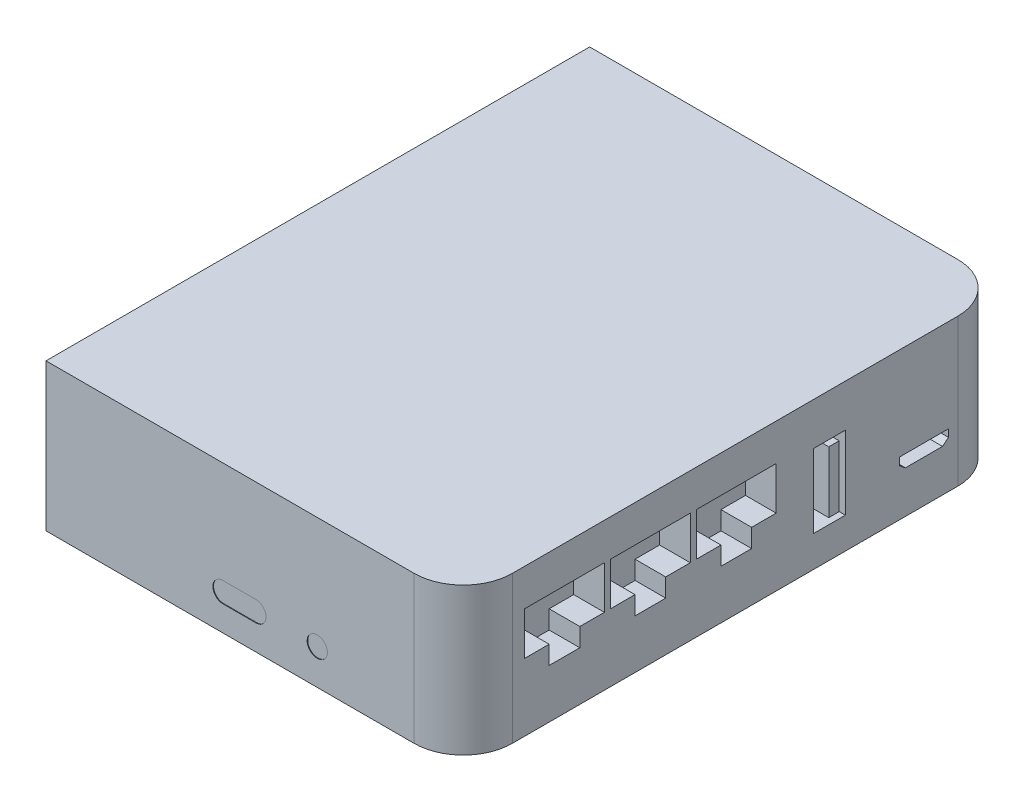
SolidWorks part; units mm, degrees
ref_plane "Plan de face" through (0, 0, 0) normal (0, 0, 1) x (1, 0, 0)
ref_plane "Plan de dessus" through (0, 0, 0) normal (0, 1, 0) x (1, 0, 0)
ref_plane "Plan de droite" through (0, 0, 0) normal (1, 0, 0) x (0, 0, -1)
sketch "Esquisse1" plane through (0, 0, 0) normal (0, 1, 0) x (1, 0, 0)
  line L1 (-34, 44.3) -> (34, 44.3)
  line L2 (-34, 44.3) -> (-34, -44.3)
  line L3 (-34, -44.3) -> (34, -44.3)
  line L4 (34, 44.3) -> (34, -44.3)
  point P4 (0, 44.3)
  point P6 (-34, 0)
  dimension "D1" = 68
  dimension "D2" = 88.6
extrude "Boss.-Extru.1" add sketch "Esquisse1" along normal blind 24
sketch "Esquisse2" plane through (34, 0, 0) normal (1, 0, 0) x (0, 0, -1)
  line L0 (-34.3, 18) -> (-34.3, 11)
  line L1 (-34.3, 11) -> (-30.3, 11)
  line L2 (-30.3, 11) -> (-30.3, 8)
  line L3 (-30.3, 8) -> (-25.3, 8)
  line L4 (-25.3, 8) -> (-25.3, 11)
  line L5 (-25.3, 11) -> (-21.3, 11)
  line L6 (-21.3, 11) -> (-21.3, 18)
  line L7 (-21.3, 18) -> (-34.3, 18)
  line L8 (-7.3, 18) -> (-20.3, 18)
  line L9 (-20.3, 18) -> (-20.3, 11)
  line L10 (-20.3, 11) -> (-16.3, 11)
  line L11 (-16.3, 11) -> (-16.3, 8)
  line L12 (-16.3, 8) -> (-11.3, 8)
  line L13 (-11.3, 8) -> (-11.3, 11)
  line L14 (-11.3, 11) -> (-7.3, 11)
  line L15 (-7.3, 11) -> (-7.3, 18)
  line L16 (6.7, 18) -> (-6.3, 18)
  line L17 (-6.3, 18) -> (-6.3, 11)
  line L18 (-6.3, 11) -> (-2.3, 11)
  line L19 (-2.3, 11) -> (-2.3, 8)
  line L20 (-2.3, 8) -> (2.7, 8)
  line L21 (2.7, 8) -> (2.7, 11)
  line L22 (2.7, 11) -> (6.7, 11)
  line L23 (6.7, 11) -> (6.7, 18)
  line L24 (26.784, 8.8649) -> (34.784, 8.8649)
  line L25 (12.7695, 17.0779) -> (17.9695, 17.0779)
  line L26 (12.7695, 17.0779) -> (12.7695, 5.0779)
  line L27 (12.7695, 5.0779) -> (17.9695, 5.0779)
  line L28 (17.9695, 17.0779) -> (17.9695, 5.0779)
  line L29 (16.9695, 16.0779) -> (15.2695, 16.0779)
  line L30 (16.9695, 16.0779) -> (16.9695, 6.0779)
  line L31 (16.9695, 6.0779) -> (15.2695, 6.0779)
  line L32 (15.2695, 16.0779) -> (15.2695, 6.0779)
  line L39 (-44.3, 24) -> (44.3, 24) construction
  line L40 (-44.3, 24) -> (-44.3, 0) construction
  line L41 (34.784, 8.8649) -> (34.784, 7.6533)
  line L42 (34.784, 7.6533) -> (33.8109, 6.8649)
  line L43 (33.8109, 6.8649) -> (27.7572, 6.8649)
  line L44 (27.7572, 6.8649) -> (26.784, 7.6533)
  line L45 (26.784, 7.6533) -> (26.784, 8.8649)
  point P33 (30.784, 6.8649)
  point P39 (16.9695, 11.0779)
  point P40 (17.9695, 11.0779)
  point P42 (30.784, 8.8649)
  dimension "D1" = 13
  dimension "D2" = 10
  dimension "D3" = 4
  dimension "D4" = 3
  dimension "D6" = 12
  dimension "D7" = 5.2
  dimension "D8" = 10
  dimension "D9" = 1.7
  dimension "D10" = 1
  dimension "D11" = 8
  dimension "D12" = 2
  dimension "D13" = 6
  dimension "D14" = 10
  dimension "D5" = 3
extrude "Enlèv. mat.-Extru.1" cut sketch "Esquisse2" against normal blind 5
sketch "Esquisse3" plane through (0, 0, -44.3) normal (0, 0, -1) x (-1, 0, 0)
  line L0 (34, 24) -> (34, 0) construction
  line L1 (-2.5, 6.8) -> (11, 6.8)
  line L2 (-2.5, 6.8) -> (-2.5, 5)
  line L3 (-2.5, 5) -> (11, 5)
  line L4 (11, 6.8) -> (11, 5)
  line L5 (-34, 0) -> (34, 0) construction
  dimension "D1" = 23
  dimension "D2" = 5
  dimension "D3" = 13.5
  dimension "D4" = 1.8
extrude "Enlèv. mat.-Extru.2" cut sketch "Esquisse3" against normal blind 5 contours L2 L1 L4 L3
sketch "Esquisse4" plane through (0, 0, 44.3) normal (0, 0, 1) x (1, 0, 0)
  line L0 (-5.1512, 5.7633) -> (0.2117, 5.7633) construction
  line L1 (-5.1512, 7.4133) -> (0.2117, 7.4133)
  line L2 (-5.1512, 4.1133) -> (0.2117, 4.1133)
  circle A0 centre (10.2117, 5.7633) radius 1.65
  arc A1 (-5.1512, 7.4133) -> (-5.1512, 4.1133) centre (-5.1512, 5.7633) ccw
  arc A2 (0.2117, 4.1133) -> (0.2117, 7.4133) centre (0.2117, 5.7633) ccw
  point P4 (-2.4698, 5.7633)
  dimension "D1" = 3.3
  dimension "D2" = 10
extrude "Enlèv. mat.-Extru.3" cut sketch "Esquisse4" against normal blind 0.1
sketch "Esquisse5" plane through (0, 0, 0) normal (0, -1, 0) x (1, 0, 0)
  line L0 (0, 0) -> (0, 12.7312) construction
  line L1 (0, 0) -> (7.7339, 0) construction
  circle A0 centre (-18.5, 37) radius 2.5
  circle A1 centre (18.5, 37) radius 2.5
  circle A2 centre (18.5, -37) radius 2.5
  circle A3 centre (-18.5, -37) radius 2.5
  dimension "D1" = 5
  dimension "D2" = 37
  dimension "D3" = 74
extrude "Boss.-Extru.3" add sketch "Esquisse5" along normal blind 1.8
fillet "Congé1" radius 8 2 edges at (34, 12, -44.3) (34, 12, 44.3)
